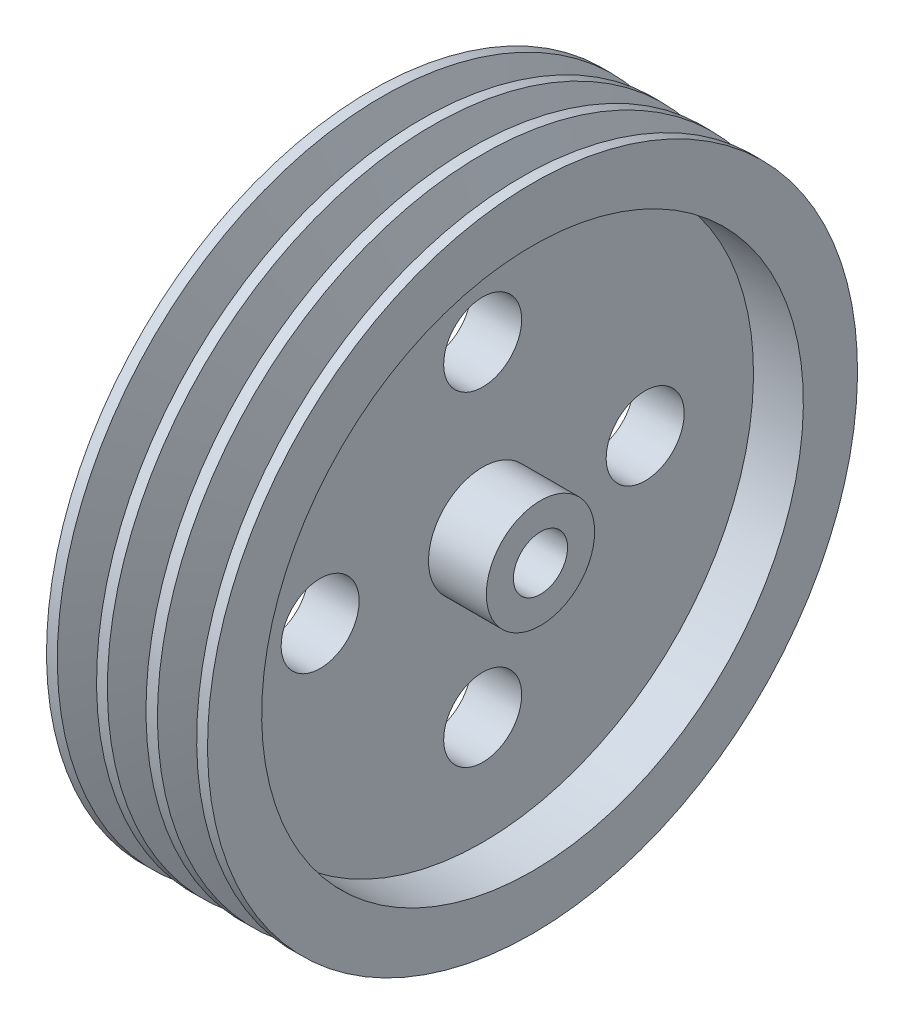
SolidWorks part; units mm, degrees
ref_plane "Front Plane" through (0, 0, 0) normal (0, 0, 1) x (1, 0, 0)
ref_plane "Top Plane" through (0, 0, 0) normal (0, 1, 0) x (1, 0, 0)
ref_plane "Right Plane" through (0, 0, 0) normal (1, 0, 0) x (0, 0, -1)
sketch "Sketch1" plane through (0, 0, 0) normal (0, 0, 1) x (1, 0, 0)
  line L1 (0, 317.5) -> (0, 635)
  line L2 (0, 635) -> (711.2, 635)
  line L3 (1981.2, 635) -> (1981.2, 317.5)
  line L5 (0, 317.5) -> (1981.2, 317.5)
  line L6 (1303.2431, 3175) -> (1887.6118, 3175)
  line L8 (1303.2431, 635) -> (1303.2431, 3175)
  line L12 (0, 0) -> (1981.2, 0) construction
  line L13 (711.2, 635) -> (711.2, 3175)
  line L14 (127, 3810) -> (0, 3810)
  line L15 (1760.6118, 3810) -> (1887.6118, 3810)
  line L16 (0, 3810) -> (0, 3175)
  line L17 (0, 3175) -> (711.2, 3175)
  line L18 (1887.6118, 3810) -> (1887.6118, 3175)
  line L19 (1303.2431, 635) -> (1981.2, 635)
  line L21 (1003.4889, 3363.0556) -> (876.4889, 3363.0556)
  line L22 (876.4889, 3363.0556) -> (713.8144, 3810)
  line L24 (127, 3810) -> (293.4072, 3352.8)
  line L25 (293.4072, 3352.8) -> (420.4072, 3352.8)
  line L26 (420.4072, 3352.8) -> (586.8144, 3810)
  line L27 (586.8144, 3810) -> (713.8144, 3810)
  line L28 (1003.4889, 3363.0556) -> (1166.1633, 3810)
  line L29 (1166.1633, 3810) -> (1300.6288, 3810)
  line L30 (1300.6288, 3810) -> (1456.1676, 3352.8)
  line L31 (1456.1676, 3352.8) -> (1583.1676, 3352.8)
  line L32 (1583.1676, 3352.8) -> (1760.6118, 3810)
  dimension "D5" = 40
  dimension "D1" = 1981.2
  dimension "D2" = 317.5
  dimension "D3" = 40
  dimension "D4" = 127
  dimension "D6" = 127
  dimension "D7" = 127
  dimension "D8" = 127
  dimension "D9" = 40
  dimension "D10" = 127
revolve "Revolve1" add sketch "Sketch1" angle 360 about L12
sketch "Sketch2" plane through (1303.2431, 0, 0) normal (1, 0, 0) x (0, 0, -1)
  line L0 (0, 0) -> (3810, 0) construction
  line L1 (0, 0) -> (0, 3810) construction
  line L2 (0, 0) -> (0, -3810) construction
  line L3 (0, 0) -> (-3810, 0) construction
  circle A0 centre (0, 1905) radius 457.2
  circle A1 centre (0, 0) radius 3810 construction
  circle A2 centre (0, -1905) radius 457.2
  circle A3 centre (1905, 0) radius 457.2
  circle A4 centre (-1905, 0) radius 457.2
  dimension "D1" = 914.4
  dimension "D2" = 914.4
  dimension "D3" = 914.4
  dimension "D4" = 914.4
extrude "Cut-Extrude1" cut sketch "Sketch2" against normal up to next
